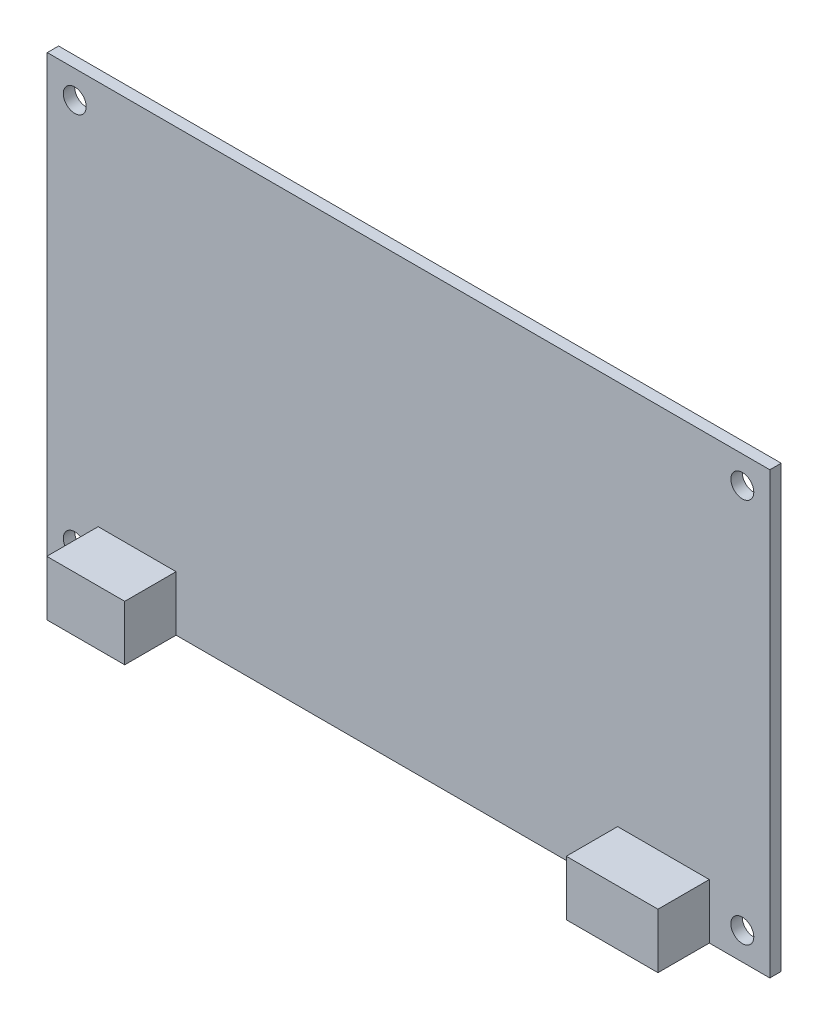
SolidWorks part; units mm, degrees
ref_plane "Front Plane" through (0, 0, 0) normal (0, 0, 1) x (1, 0, 0)
ref_plane "Top Plane" through (0, 0, 0) normal (0, 1, 0) x (1, 0, 0)
ref_plane "Right Plane" through (0, 0, 0) normal (1, 0, 0) x (0, 0, -1)
sketch "Sketch1" plane through (0, 0, 0) normal (0, 0, 1) x (1, 0, 0)
  line L0 (100.076, 60.96) -> (0, 0) construction
  line L1 (0, 0) -> (100.076, 0)
  line L2 (0, 0) -> (0, 60.96)
  line L3 (0, 60.96) -> (100.076, 60.96)
  line L4 (100.076, 0) -> (100.076, 60.96)
  line L6 (96.266, 3.81) -> (3.81, 3.81) construction
  line L7 (96.266, 3.81) -> (96.266, 57.15) construction
  line L8 (96.266, 57.15) -> (3.81, 57.15) construction
  line L9 (3.81, 3.81) -> (3.81, 57.15) construction
  line L10 (96.266, 3.81) -> (3.81, 57.15) construction
  line L11 (96.266, 57.15) -> (3.81, 3.81) construction
  circle A0 centre (3.81, 57.15) radius 1.5875
  circle A1 centre (96.266, 57.15) radius 1.5875
  circle A2 centre (96.266, 3.81) radius 1.5875
  circle A3 centre (3.81, 3.81) radius 1.5875
  point P5 (50.038, 30.48)
  dimension "D4" = 3.175
  dimension "D1" = 60.96
  dimension "D2" = 100.076
  dimension "D3" = 3.81
  dimension "D5" = 3.81
extrude "Boss-Extrude1" add sketch "Sketch1" along normal blind 1.5748
sketch "Sketch2" plane through (0, 0, 1.5748) normal (0, 0, 1) x (1, 0, 0)
  line L0 (0, 0) -> (100.076, 0) construction
  line L1 (7.0485, 7.62) -> (17.8435, 7.62)
  line L2 (7.0485, 7.62) -> (7.0485, 0)
  line L3 (7.0485, 0) -> (17.8435, 0)
  line L4 (17.8435, 7.62) -> (17.8435, 0)
  line L5 (7.0485, 7.62) -> (17.8435, 0) construction
  line L6 (7.0485, 0) -> (17.8435, 7.62) construction
  line L7 (0, 60.96) -> (0, 0) construction
  line L9 (78.994, 7.62) -> (91.694, 7.62)
  line L10 (78.994, 7.62) -> (78.994, 0)
  line L11 (78.994, 0) -> (91.694, 0)
  line L12 (91.694, 7.62) -> (91.694, 0)
  line L13 (78.994, 7.62) -> (91.694, 0) construction
  line L14 (78.994, 0) -> (91.694, 7.62) construction
  point P0 (12.446, 3.81)
  point P9 (85.344, 3.81)
  dimension "D1" = 10.795
  dimension "D2" = 7.62
  dimension "D3" = 12.446
  dimension "D4" = 85.344
  dimension "D5" = 7.62
  dimension "D6" = 12.7
extrude "Boss-Extrude2" add sketch "Sketch2" along normal blind 7.112
